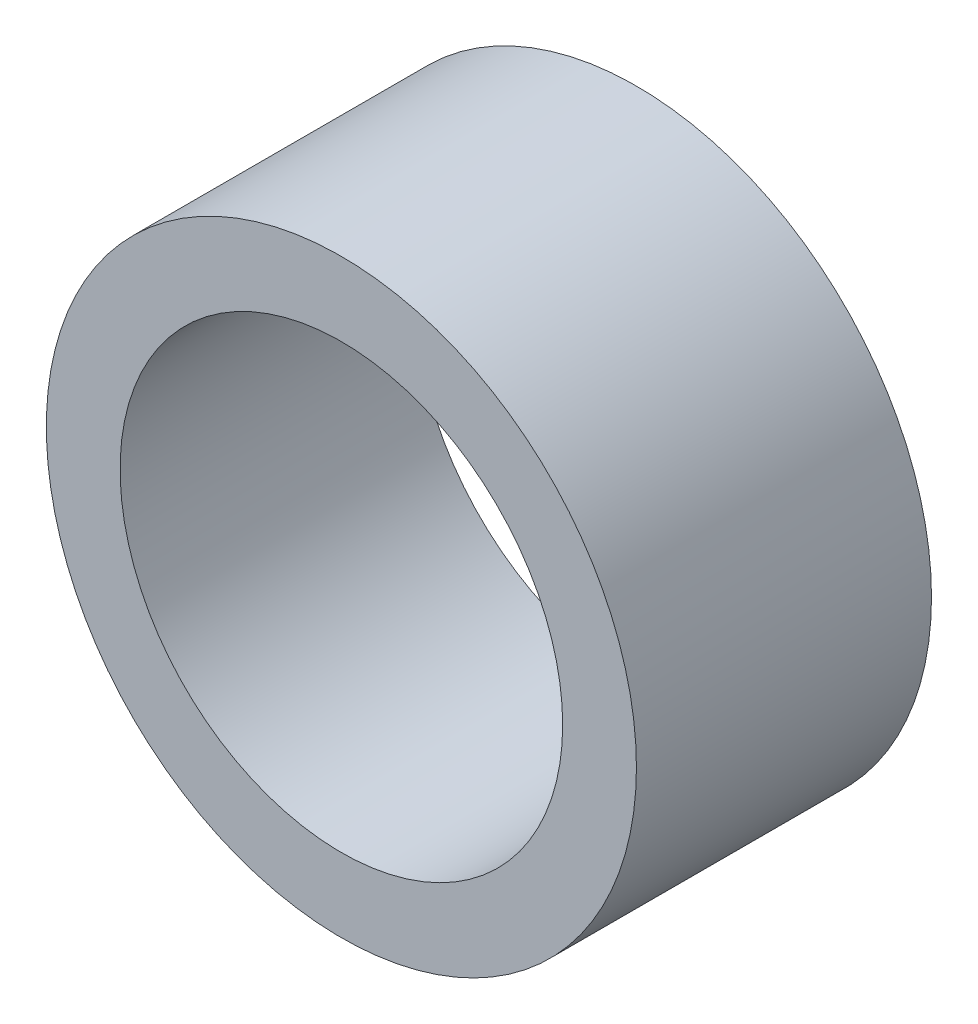
SolidWorks part; units mm, degrees
ref_plane "前视基准面" through (0, 0, 0) normal (0, 0, 1) x (1, 0, 0)
ref_plane "上视基准面" through (0, 0, 0) normal (0, 1, 0) x (1, 0, 0)
ref_plane "右视基准面" through (0, 0, 0) normal (1, 0, 0) x (0, 0, -1)
other "Configuration Table"
sketch "草图1" plane through (0, 0, 0) normal (0, 0, 1) x (1, 0, 0)
  circle A0 centre (0, 10) radius 3
  circle A1 centre (0, 10) radius 4
  dimension "D1" = 6
  dimension "D2" = 8
extrude "凸台-拉伸1" add sketch "草图1" along normal blind 4
